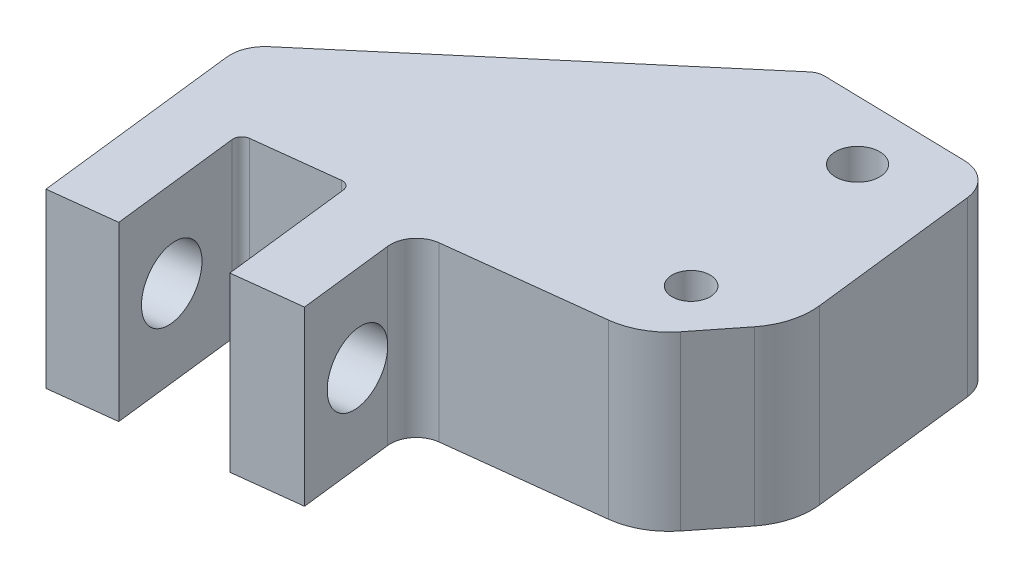
SolidWorks part; units mm, degrees
ref_plane "Front Plane" through (0, 0, 0) normal (0, 0, 1) x (1, 0, 0)
ref_plane "Top Plane" through (0, 0, 0) normal (0, 1, 0) x (1, 0, 0)
ref_plane "Right Plane" through (0, 0, 0) normal (1, 0, 0) x (0, 0, -1)
sketch "Sketch1" plane through (0, 0, 0) normal (0, 1, 0) x (1, 0, 0)
  line L0 (-0.1457, -11.8849) -> (-0.7864, -6.4224)
  line L1 (0.5287, -4.7579) -> (9.3116, -3.7278)
  line L2 (11.9843, -2.2348) -> (13.8753, 0.1586)
  line L3 (14.7094, 3.1043) -> (13.5696, 12.8233)
  line L4 (11.629, 14.5898) -> (3.3434, 14.7794)
  line L5 (2.6727, 14.5415) -> (-14.2527, 0.1475)
  line L6 (-14.9434, -1.609) -> (-13.5539, -13.4574)
  line L7 (-13.5539, -13.4574) -> (-9.7797, -13.0148)
  line L8 (-9.7797, -13.0148) -> (-10.6533, -5.5658)
  line L9 (-10.215, -5.011) -> (-5.4476, -4.4519)
  line L10 (-4.8928, -4.8903) -> (-4.0192, -12.3392)
  line L11 (-4.0192, -12.3392) -> (-0.1457, -11.8849)
  circle A0 centre (9.9947, 0.3797) radius 1.1
  circle A1 centre (8.7134, 11.3048) radius 1.275
  arc A2 (0.5287, -4.7579) -> (-0.7864, -6.4224) centre (0.7034, -6.2477) ccw
  arc A3 (9.3116, -3.7278) -> (11.9843, -2.2348) centre (8.8457, 0.245) ccw
  arc A4 (13.8753, 0.1586) -> (14.7094, 3.1043) centre (10.7367, 2.6384) ccw
  arc A5 (13.5696, 12.8233) -> (11.629, 14.5898) centre (11.5832, 12.5904) ccw
  arc A6 (3.3434, 14.7794) -> (2.6727, 14.5415) centre (3.3205, 13.7797) ccw
  arc A7 (-14.2527, 0.1475) -> (-14.9434, -1.609) centre (-12.957, -1.376) ccw
  arc A8 (-10.215, -5.011) -> (-10.6533, -5.5658) centre (-10.1567, -5.5076) ccw
  arc A9 (-4.8928, -4.8903) -> (-5.4476, -4.4519) centre (-5.3894, -4.9485) ccw
  dimension "D1" = 2.2
  dimension "D2" = 2.55
  dimension "D3" = 1.5
  dimension "D4" = 4
  dimension "D5" = 2
  dimension "D6" = 1
  dimension "D7" = 0.5
  dimension "D8" = 0.5287
  dimension "D9" = 0.7034
  dimension "D10" = 2.6727
  dimension "D11" = 3.3205
  dimension "D12" = 3.3434
  dimension "D13" = 8.7134
  dimension "D14" = 8.8457
  dimension "D15" = 10.7367
  dimension "D16" = 9.9947
  dimension "D17" = 11.5832
  dimension "D18" = 11.9843
  dimension "D19" = 0.1457
  dimension "D20" = 4.0192
  dimension "D21" = 9.7797
  dimension "D22" = 12.957
  dimension "D23" = 0.1475
  dimension "D26" = 0.3797
  dimension "D29" = 11.3048
extrude "Boss-Extrude1" add sketch "Sketch1" along normal blind 10 contours L0 A2 L1 A3 L2 A4 L3 A5 L4 A6 L5 A7 L6 L7 L8 A8 L9 A9 L10 L11
sketch "Sketch2" plane through (-1.5187, 0, 0.1781) normal (0.9932, 0, -0.1165) x (-0.1165, 0, -0.9932)
  line L0 (-11.7871, 10) -> (-4.7871, 0) construction
  circle A0 centre (-8.2871, 5) radius 2
  dimension "D1" = 4
extrude "Cut-Extrude1" cut sketch "Sketch2" against normal up to surface (13.5 mm away) up to face at (-14.2486, 5, 7.5332)
